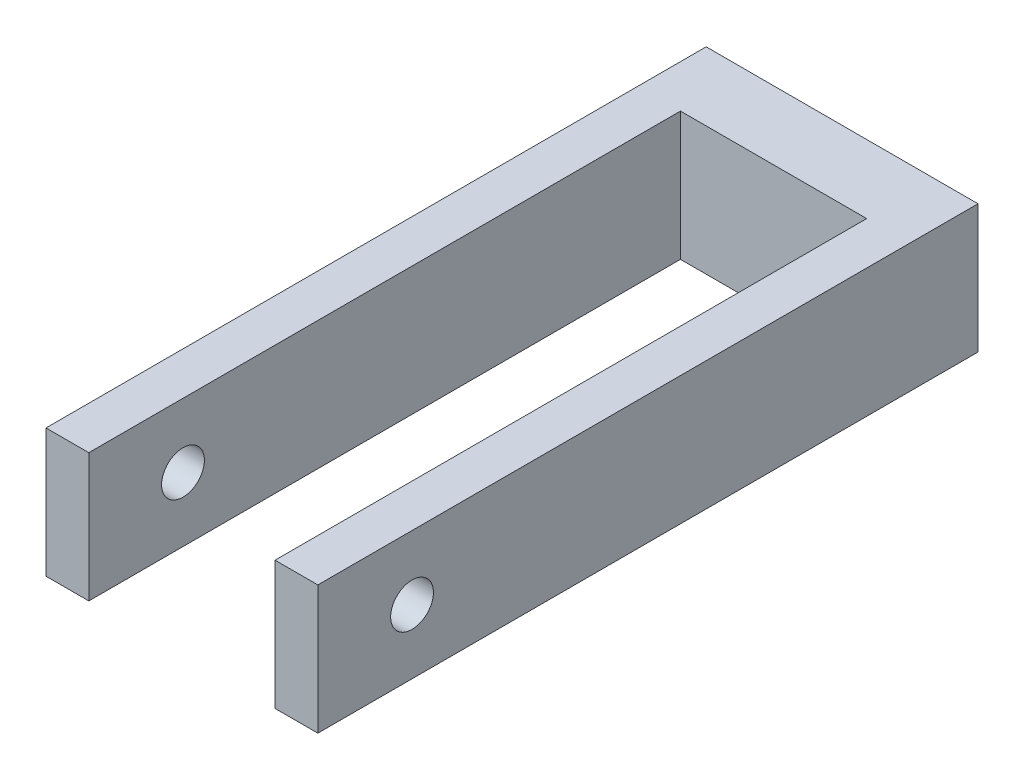
SolidWorks part; units mm, degrees
ref_plane "Front Plane" through (0, 0, 0) normal (0, 0, 1) x (1, 0, 0)
ref_plane "Top Plane" through (0, 0, 0) normal (0, 1, 0) x (1, 0, 0)
ref_plane "Right Plane" through (0, 0, 0) normal (1, 0, 0) x (0, 0, -1)
sketch "Sketch1" plane through (0, 0, 0) normal (0, 0, 1) x (1, 0, 0)
  line L0 (-16.8014, 8.169) -> (14.9486, 8.169)
  line L1 (14.9486, 8.169) -> (14.9486, -6.831)
  line L2 (14.9486, -6.831) -> (-16.8014, -6.831)
  line L3 (-16.8014, -6.831) -> (-16.8014, 8.169)
  dimension "D1" = 31.75
  dimension "D2" = 15
extrude "Boss-Extrude1" add sketch "Sketch1" along normal blind 8
sketch "Sketch2" plane through (0, 0, 8) normal (0, 0, 1) x (1, 0, 0)
  line L0 (-16.8014, 8.169) -> (-11.8014, 8.169)
  line L1 (14.9486, 8.169) -> (-16.8014, 8.169) construction
  line L2 (-11.8014, 8.169) -> (-11.8014, -6.831)
  line L3 (-16.8014, -6.831) -> (14.9486, -6.831) construction
  line L4 (-11.8014, -6.831) -> (-16.8014, -6.831)
  line L5 (-16.8014, -6.831) -> (-16.8014, 8.169)
  line L6 (14.9486, 8.169) -> (9.9486, 8.169)
  line L7 (9.9486, 8.169) -> (9.9486, -6.831)
  line L8 (9.9486, -6.831) -> (14.9486, -6.831)
  line L9 (14.9486, -6.831) -> (14.9486, 8.169)
  dimension "D1" = 5
  dimension "D2" = 5
extrude "Boss-Extrude2" add sketch "Sketch2" along normal blind 69.1
sketch "Sketch3" plane through (14.9486, 0, 0) normal (1, 0, 0) x (0, 0, -1)
  line L0 (-77.1, -6.831) -> (-77.1, 8.169) construction
  circle A0 centre (-66.1, 0.669) radius 2.5
  dimension "D1" = 5
  dimension "D2" = 11
extrude "Cut-Extrude1" cut sketch "Sketch3" against normal blind 69.1
sketch "Sketch4" plane through (0, 0, 0) normal (0, 0, -1) x (-1, 0, 0)
  circle A0 centre (0.9264, 0.669) radius 4
  circle A1 centre (0.9264, 0.669) radius 2
  dimension "D1" = 8
  dimension "D2" = 4
extrude "Cut-Extrude3" cut sketch "Sketch4" against normal blind 4
sketch "Sketch5" plane through (0, -6.831, 0) normal (0, -1, 0) x (1, 0, 0)
  line L0 (-0.9264, 0) -> (-0.9264, 8) construction
  line L1 (-16.8014, 0) -> (14.9486, 0) construction
  line L2 (-11.8014, 8) -> (9.9486, 8) construction
  circle A0 centre (-0.9264, 4) radius 1.5
  point P9 (-0.9264, 4)
  dimension "D1" = 3
extrude "Cut-Extrude4" cut sketch "Sketch5" against normal blind 3
